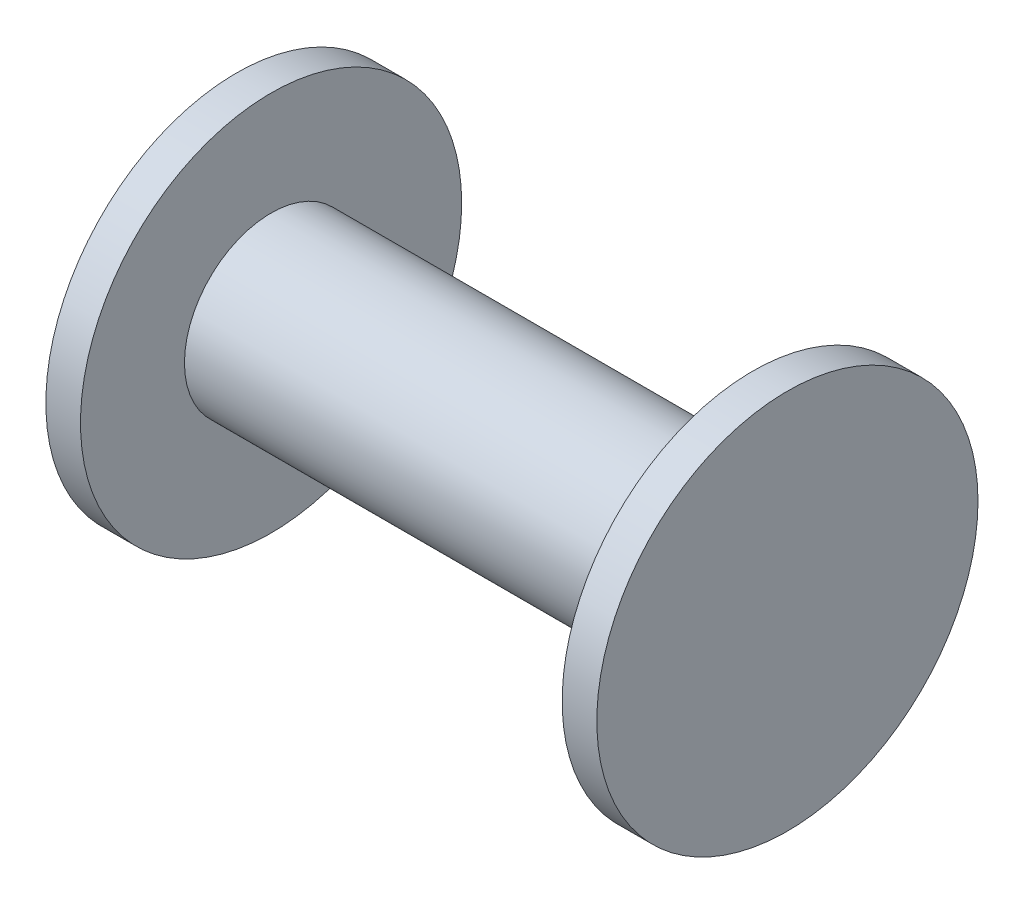
SolidWorks part; units mm, degrees
material "GR250"
ref_plane "Front Plane" through (0, 0, 0) normal (0, 0, 1) x (1, 0, 0)
ref_plane "Top Plane" through (0, 0, 0) normal (0, 1, 0) x (1, 0, 0)
ref_plane "Right Plane" through (0, 0, 0) normal (1, 0, 0) x (0, 0, -1)
sketch "Sketch1" plane through (0, 0, 0) normal (1, 0, 0) x (0, 0, -1)
  circle A0 centre (0, 0) radius 5
  dimension "D1" = 10
extrude "Boss-Extrude1" add sketch "Sketch1" along normal mid plane 31.8
sketch "Sketch2" plane through (15.9, 0, 0) normal (1, 0, 0) x (0, 0, -1)
  circle A0 centre (0, 0) radius 11
  dimension "D1" = 22
extrude "Boss-Extrude2" add sketch "Sketch2" against normal blind 2
mirror "Mirror1" about plane through (0, 0, 0) normal (1, 0, 0) of "Boss-Extrude2"
